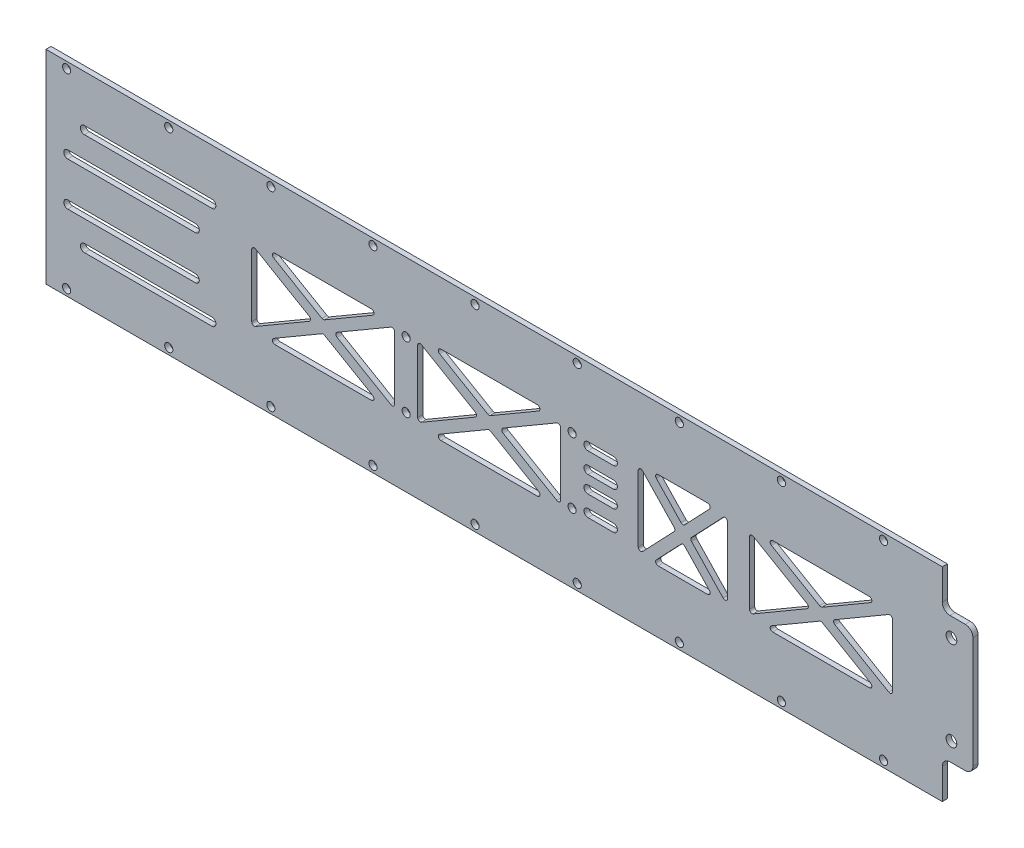
SolidWorks part; units mm, degrees
material "玻"
ref_plane "前视基准面" through (0, 0, 0) normal (0, 0, 1) x (1, 0, 0)
ref_plane "上视基准面" through (0, 0, 0) normal (0, 1, 0) x (1, 0, 0)
ref_plane "右视基准面" through (0, 0, 0) normal (1, 0, 0) x (0, 0, -1)
sketch "草图1" plane through (0, 0, 0) normal (0, 0, 1) x (1, 0, 0)
  line L0 (177.5, -27.83) -> (177.5, -39.83)
  line L1 (-177.5, 39.83) -> (177.5, 39.83)
  line L2 (-177.5, 39.83) -> (-177.5, -39.83)
  line L3 (-177.5, -39.83) -> (177.5, -39.83)
  line L4 (177.5, 39.83) -> (177.5, 27.83)
  line L5 (-177.5, 39.83) -> (177.5, -39.83) construction
  line L6 (-177.5, -39.83) -> (177.5, 39.83) construction
  line L7 (180.5, 24.83) -> (186.5, 24.83)
  line L9 (180.5, -24.83) -> (186.5, -24.83)
  line L10 (189.5, 21.83) -> (189.5, -21.83)
  arc A0 (186.5, -24.83) -> (189.5, -21.83) centre (186.5, -21.83) ccw
  arc A1 (186.5, 24.83) -> (189.5, 21.83) centre (186.5, 21.83) cw
  arc A2 (177.5, -27.83) -> (180.5, -24.83) centre (180.5, -27.83) cw
  arc A3 (180.5, 24.83) -> (177.5, 27.83) centre (180.5, 27.83) cw
  point P0 (0, 0)
  point P12 (189.5, -24.83)
  point P17 (177.5, -24.83)
  dimension "D6" = 3
  dimension "D1" = 79.66
  dimension "D2" = 355
  dimension "D3" = 15
  dimension "D4" = 15
  dimension "D5" = 12
extrude "凸台-拉伸1" add sketch "草图1" along normal blind 2
sketch "草图2" plane through (0, 0, 0) normal (0, 0, -1) x (-1, 0, 0)
  line L0 (0, 0) -> (157.1428, 0) construction
  line L1 (0, 0) -> (0, 112.2991) construction
  line L2 (-177.5, 39.83) -> (177.5, 39.83) construction
  line L3 (177.5, 39.83) -> (177.5, -39.83) construction
  line L4 (-189.5, -21.83) -> (-189.5, 21.83) construction
  line L5 (177.5, 39.83) -> (177.5, -39.83) construction
  circle A1 centre (165.5, 37.3) radius 1.6
  circle A2 centre (125.5, 37.3) radius 1.6
  circle A3 centre (85.5, 37.3) radius 1.6
  circle A4 centre (45.5, 37.3) radius 1.6
  circle A5 centre (5.5, 37.3) radius 1.6
  circle A6 centre (-34.5, 37.3) radius 1.6
  circle A7 centre (-74.5, 37.3) radius 1.6
  circle A8 centre (-114.5, 37.3) radius 1.6
  circle A9 centre (-154.5, 37.3) radius 1.6
  circle A10 centre (-154.5, -37.3) radius 1.6
  circle A11 centre (-114.5, -37.3) radius 1.6
  circle A12 centre (-74.5, -37.3) radius 1.6
  circle A13 centre (-34.5, -37.3) radius 1.6
  circle A14 centre (5.5, -37.3) radius 1.6
  circle A15 centre (45.5, -37.3) radius 1.6
  circle A16 centre (85.5, -37.3) radius 1.6
  circle A17 centre (125.5, -37.3) radius 1.6
  circle A18 centre (165.5, -37.3) radius 1.6
  circle A19 centre (-181.1, 17.5) radius 2.1
  circle A20 centre (-181.1, -17.5) radius 2.1
  circle A21 centre (141.2, 18.5) radius 2.1
  circle A22 centre (141.2, -18.5) radius 2.1
  circle A23 centre (98.9, 17.5) radius 2.1
  circle A24 centre (98.9, -17.5) radius 2.1
  circle A25 centre (32.5, 12.83) radius 1.6
  circle A26 centre (-32.5, 12.83) radius 1.6
  circle A27 centre (-32.5, -12.83) radius 1.6
  circle A28 centre (32.5, -12.83) radius 1.6
  dimension "D1" = 3.2
  dimension "D2" = 12
  dimension "D3" = 37.3
  dimension "D5" = 40
  dimension "D6" = 4.2
  dimension "D7" = 8.4
  dimension "D8" = 17.5
  dimension "D9" = 4.2
  dimension "D10" = 36.3
  dimension "D11" = 18.5
  dimension "D12" = 4.2
  dimension "D13" = 78.6
  dimension "D14" = 17.5
  dimension "D15" = 3.2
  dimension "D16" = 27
  dimension "D17" = 145
  dimension "D19" = 65
  dimension "D4" = 9
  dimension "D18" = 2
extrude "切除-拉伸1" cut sketch "草图2" against normal through all
sketch "草图4" plane through (0, 0, 2) normal (0, 0, 1) x (1, 0, 0)
  line L0 (-30, 15.5) -> (30, 15.5)
  line L1 (-30, 17.5) -> (30, 17.5)
  line L2 (-30, 17.5) -> (-30, -17.5)
  line L3 (-30, -17.5) -> (30, -17.5)
  line L4 (30, 17.5) -> (30, -17.5)
  line L5 (-30, 17.5) -> (30, -17.5) construction
  line L6 (-30, -17.5) -> (30, 17.5) construction
  line L7 (-31.0077, 15.7724) -> (28.9923, -19.2276)
  line L8 (-28.9923, -19.2276) -> (31.0077, 15.7724)
  line L9 (-32, 17.5) -> (-32, -17.5)
  line L10 (-30, -19.5) -> (30, -19.5)
  line L11 (28, 17.5) -> (28, -17.5)
  line L12 (-30, 19.5) -> (30, 19.5)
  line L13 (-28.9923, 19.2276) -> (31.0077, -15.7724)
  line L14 (-31.0077, -15.7724) -> (28.9923, 19.2276)
  line L15 (-28, 17.5) -> (-28, -17.5)
  line L16 (-30, -15.5) -> (30, -15.5)
  line L17 (32, 17.5) -> (32, -17.5)
  line L18 (35, 15.5) -> (95, 15.5)
  line L19 (35, 17.5) -> (95, 17.5)
  line L20 (35, 17.5) -> (35, -17.5)
  line L21 (35, -17.5) -> (95, -17.5)
  line L22 (95, 17.5) -> (95, -17.5)
  line L23 (33.9923, 15.7724) -> (93.9923, -19.2276)
  line L24 (36.0077, -19.2276) -> (96.0077, 15.7724)
  line L25 (33, 17.5) -> (33, -17.5)
  line L26 (35, -19.5) -> (95, -19.5)
  line L27 (93, 17.5) -> (93, -17.5)
  line L28 (35, 19.5) -> (95, 19.5)
  line L29 (36.0077, 19.2276) -> (96.0077, -15.7724)
  line L30 (33.9923, -15.7724) -> (93.9923, 19.2276)
  line L31 (37, 17.5) -> (37, -17.5)
  line L32 (35, -15.5) -> (95, -15.5)
  line L33 (97, 17.5) -> (97, -17.5)
  line L34 (35, 17.5) -> (95, -17.5) construction
  line L35 (35, -17.5) -> (95, 17.5) construction
  line L36 (-95, 15.5) -> (-35, 15.5)
  line L37 (-95, 17.5) -> (-35, 17.5)
  line L38 (-95, 17.5) -> (-95, -17.5)
  line L39 (-95, -17.5) -> (-35, -17.5)
  line L40 (-35, 17.5) -> (-35, -17.5)
  line L41 (-96.0077, 15.7724) -> (-36.0077, -19.2276)
  line L42 (-93.9923, -19.2276) -> (-33.9923, 15.7724)
  line L43 (-97, 17.5) -> (-97, -17.5)
  line L44 (-95, -19.5) -> (-35, -19.5)
  line L45 (-37, 17.5) -> (-37, -17.5)
  line L46 (-95, 19.5) -> (-35, 19.5)
  line L47 (-93.9923, 19.2276) -> (-33.9923, -15.7724)
  line L48 (-96.0077, -15.7724) -> (-36.0077, 19.2276)
  line L49 (-93, 17.5) -> (-93, -17.5)
  line L50 (-95, -15.5) -> (-35, -15.5)
  line L51 (-33, 17.5) -> (-33, -17.5)
  line L52 (-95, 17.5) -> (-35, -17.5) construction
  line L53 (-95, -17.5) -> (-35, 17.5) construction
  line L54 (100, 15.5) -> (160, 15.5)
  line L55 (100, 17.5) -> (160, 17.5)
  line L56 (100, 17.5) -> (100, -17.5)
  line L57 (100, -17.5) -> (160, -17.5)
  line L58 (160, 17.5) -> (160, -17.5)
  line L59 (98.9923, 15.7724) -> (158.9923, -19.2276)
  line L60 (101.0077, -19.2276) -> (161.0077, 15.7724)
  line L61 (98, 17.5) -> (98, -17.5)
  line L62 (100, -19.5) -> (160, -19.5)
  line L63 (158, 17.5) -> (158, -17.5)
  line L64 (100, 19.5) -> (160, 19.5)
  line L65 (101.0077, 19.2276) -> (161.0077, -15.7724)
  line L66 (98.9923, -15.7724) -> (158.9923, 19.2276)
  line L67 (102, 17.5) -> (102, -17.5)
  line L68 (100, -15.5) -> (160, -15.5)
  line L69 (162, 17.5) -> (162, -17.5)
  line L70 (100, 17.5) -> (160, -17.5) construction
  line L71 (100, -17.5) -> (160, 17.5) construction
  line L72 (0, 0) -> (267.4149, 0) construction
  line L73 (-127.5, -17.5) -> (-112.5, -17.5)
  line L74 (-127.5, -17.5) -> (-127.5, 17.5)
  line L75 (-127.5, 17.5) -> (-112.5, 17.5)
  line L76 (-112.5, -17.5) -> (-112.5, 17.5)
  line L77 (-127.5, -17.5) -> (-112.5, 17.5) construction
  line L78 (-127.5, 17.5) -> (-112.5, -17.5) construction
  line L79 (0, 0) -> (0, 160.2429) construction
  line L80 (-177.5, 39.83) -> (-177.5, -39.83) construction
  line L81 (-167.5, -17.5) -> (-167.5, 17.5)
  line L82 (-167.5, -17.5) -> (-152.5, -17.5)
  line L83 (-152.5, -17.5) -> (-152.5, 17.5)
  line L84 (-167.5, 17.5) -> (-152.5, 17.5)
  arc A0 (-30, 15.5) -> (-30, 19.5) centre (-30, 17.5) cw
  arc A1 (30, 15.5) -> (30, 19.5) centre (30, 17.5) ccw
  arc A2 (-31.0077, 15.7724) -> (-28.9923, 19.2276) centre (-30, 17.5) cw
  arc A3 (28.9923, -19.2276) -> (31.0077, -15.7724) centre (30, -17.5) ccw
  arc A4 (-28.9923, -19.2276) -> (-31.0077, -15.7724) centre (-30, -17.5) cw
  arc A5 (31.0077, 15.7724) -> (28.9923, 19.2276) centre (30, 17.5) ccw
  arc A6 (-32, 17.5) -> (-28, 17.5) centre (-30, 17.5) cw
  arc A7 (-32, -17.5) -> (-28, -17.5) centre (-30, -17.5) ccw
  arc A8 (-30, -19.5) -> (-30, -15.5) centre (-30, -17.5) cw
  arc A9 (30, -19.5) -> (30, -15.5) centre (30, -17.5) ccw
  arc A10 (28, 17.5) -> (32, 17.5) centre (30, 17.5) cw
  arc A11 (28, -17.5) -> (32, -17.5) centre (30, -17.5) ccw
  arc A12 (35, 15.5) -> (35, 19.5) centre (35, 17.5) cw
  arc A13 (95, 15.5) -> (95, 19.5) centre (95, 17.5) ccw
  arc A14 (33.9923, 15.7724) -> (36.0077, 19.2276) centre (35, 17.5) cw
  arc A15 (93.9923, -19.2276) -> (96.0077, -15.7724) centre (95, -17.5) ccw
  arc A16 (36.0077, -19.2276) -> (33.9923, -15.7724) centre (35, -17.5) cw
  arc A17 (96.0077, 15.7724) -> (93.9923, 19.2276) centre (95, 17.5) ccw
  arc A18 (33, 17.5) -> (37, 17.5) centre (35, 17.5) cw
  arc A19 (33, -17.5) -> (37, -17.5) centre (35, -17.5) ccw
  arc A20 (35, -19.5) -> (35, -15.5) centre (35, -17.5) cw
  arc A21 (95, -19.5) -> (95, -15.5) centre (95, -17.5) ccw
  arc A22 (93, 17.5) -> (97, 17.5) centre (95, 17.5) cw
  arc A23 (93, -17.5) -> (97, -17.5) centre (95, -17.5) ccw
  arc A24 (-95, 15.5) -> (-95, 19.5) centre (-95, 17.5) cw
  arc A25 (-35, 15.5) -> (-35, 19.5) centre (-35, 17.5) ccw
  arc A26 (-96.0077, 15.7724) -> (-93.9923, 19.2276) centre (-95, 17.5) cw
  arc A27 (-36.0077, -19.2276) -> (-33.9923, -15.7724) centre (-35, -17.5) ccw
  arc A28 (-93.9923, -19.2276) -> (-96.0077, -15.7724) centre (-95, -17.5) cw
  arc A29 (-33.9923, 15.7724) -> (-36.0077, 19.2276) centre (-35, 17.5) ccw
  arc A30 (-97, 17.5) -> (-93, 17.5) centre (-95, 17.5) cw
  arc A31 (-97, -17.5) -> (-93, -17.5) centre (-95, -17.5) ccw
  arc A32 (-95, -19.5) -> (-95, -15.5) centre (-95, -17.5) cw
  arc A33 (-35, -19.5) -> (-35, -15.5) centre (-35, -17.5) ccw
  arc A34 (-37, 17.5) -> (-33, 17.5) centre (-35, 17.5) cw
  arc A35 (-37, -17.5) -> (-33, -17.5) centre (-35, -17.5) ccw
  arc A36 (100, 15.5) -> (100, 19.5) centre (100, 17.5) cw
  arc A37 (160, 15.5) -> (160, 19.5) centre (160, 17.5) ccw
  arc A38 (98.9923, 15.7724) -> (101.0077, 19.2276) centre (100, 17.5) cw
  arc A39 (158.9923, -19.2276) -> (161.0077, -15.7724) centre (160, -17.5) ccw
  arc A40 (101.0077, -19.2276) -> (98.9923, -15.7724) centre (100, -17.5) cw
  arc A41 (161.0077, 15.7724) -> (158.9923, 19.2276) centre (160, 17.5) ccw
  arc A42 (98, 17.5) -> (102, 17.5) centre (100, 17.5) cw
  arc A43 (98, -17.5) -> (102, -17.5) centre (100, -17.5) ccw
  arc A44 (100, -19.5) -> (100, -15.5) centre (100, -17.5) cw
  arc A45 (160, -19.5) -> (160, -15.5) centre (160, -17.5) ccw
  arc A46 (158, 17.5) -> (162, 17.5) centre (160, 17.5) cw
  arc A47 (158, -17.5) -> (162, -17.5) centre (160, -17.5) ccw
  point P0 (0, 0)
  point P30 (-120, 0)
  point P31 (65, 0)
  point P60 (130, 0)
  point P61 (-65, 0)
  dimension "D1" = 60
  dimension "D2" = 35
  dimension "D6" = 1
  dimension "D8" = 1
  dimension "D10" = 1
  dimension "D11" = 15
  dimension "D12" = 35
  dimension "D13" = 50
  dimension "D15" = 25
  dimension "D3" = 2
  dimension "D4" = 2
  dimension "D5" = 2
  dimension "D7" = 2
  dimension "D9" = 2
  dimension "D14" = 2
extrude "切除-拉伸2" cut sketch "草图4" against normal through all contours L13 L14 L0 | L7 L15 L14 | L8 L13 L11 | L8 L16 L7 | L29 L30 L18 | L23 L31 L30 | L24 L29 L27 | L24 L32 L23 | L47 L48 L36 | L41 L49 L48 | L42 L47 L45 | L42 L50 L41 | L65 L66 L54 | L59 L67 L66 | L60 L68 L59 | L60 L65 L63 | L84 L81 L82 L83 | L73 L76 L75 L74
fillet "圆角1" radius 1 56 edges at (-28, -14.0179, 1) (-3.9693, 0, 1) (28, -14.0179, 1) (3.9693, 0, 1) (28, 14.0179, 1) (22.6022, -15.5, 1) (-22.6022, -15.5, 1) (0, -2.3154, 1) (-28, 14.0179, 1) (22.6022, 15.5, 1) (0, 2.3154, 1) (-22.6022, 15.5, 1) (87.6022, -15.5, 1) (42.3978, -15.5, 1) (65, -2.3154, 1) (93, -14.0179, 1) (68.9693, 0, 1) (93, 14.0179, 1) (37, -14.0179, 1) (37, 14.0179, 1) (61.0307, 0, 1) (87.6022, 15.5, 1) (65, 2.3154, 1) (42.3978, 15.5, 1) (-42.3978, -15.5, 1) (-87.6022, -15.5, 1) (-65, -2.3154, 1) (-37, -14.0179, 1) (-61.0307, 0, 1) (-37, 14.0179, 1) (-93, -14.0179, 1) (-93, 14.0179, 1) (-68.9693, 0, 1) (-42.3978, 15.5, 1) (-65, 2.3154, 1) (-87.6022, 15.5, 1) (152.6022, -15.5, 1) (107.3978, -15.5, 1) (130, -2.3154, 1) (102, -14.0179, 1) (102, 14.0179, 1) (126.0307, 0, 1) (158, -14.0179, 1) (133.9693, 0, 1) (158, 14.0179, 1) (152.6022, 15.5, 1) (130, 2.3154, 1) (107.3978, 15.5, 1) (-127.5, -17.5, 1) (-112.5, 17.5, 1) (-112.5, -17.5, 1) (-127.5, 17.5, 1) (-152.5, -17.5, 1) (-167.5, -17.5, 1) (-152.5, 17.5, 1) (-167.5, 17.5, 1)
sketch "草图6" plane through (0, 0, 2) normal (0, 0, 1) x (1, 0, 0)
  line L0 (181.1, 17.5) -> (181.1, -17.5)
  line L1 (114.5, 37.3) -> (154.5, 37.3)
  line L2 (-165.5, 37.3) -> (-177.5, 37.3)
  line L3 (-177.5, 39.83) -> (-177.5, -39.83) construction
  line L4 (181.1, 17.5) -> (189.5, 17.5)
  line L5 (189.5, -21.83) -> (189.5, 21.83) construction
  line L6 (114.5, 37.3) -> (114.5, 39.83)
  line L7 (177.5, 39.83) -> (-177.5, 39.83) construction
  line L8 (154.5, 37.3) -> (154.5, -37.3)
  line L9 (32.5, 12.83) -> (32.5, -12.83)
  line L10 (32.5, 12.83) -> (-32.5, 12.83)
  line L11 (-98.9, 17.5) -> (-98.9, -17.5)
  line L12 (-141.2, 18.5) -> (-98.9, 17.5)
  line L13 (-32.5, 12.83) -> (-177.5, 12.83)
  line L14 (-98.9, -17.5) -> (-177.5, -17.5)
  dimension "D1" = 35
  dimension "D2" = 12
  dimension "D3" = 40
  dimension "D4" = 8.4
  dimension "D5" = 2.53
  dimension "D6" = 74.6
  dimension "D7" = 25.66
  dimension "D8" = 65
  dimension "D9" = 35
  dimension "D10" = 145
  dimension "D11" = 78.6
sketch "草图7" plane through (0, 0, 0) normal (0, 0, 1) x (1, 0, 0)
  line L0 (37, 12.2769) -> (37, -12.2769) construction
  line L1 (37, 17.3182) -> (93.0723, 17.3182)
  line L2 (37, 17.3182) -> (37, -17.8709)
  line L3 (37, -17.8709) -> (93.0723, -17.8709)
  line L4 (93.0723, 17.3182) -> (93.0723, -17.8709)
  dimension "D1" = 0
extrude "凸台-拉伸2" add sketch "草图7" along normal blind 2
sketch "草图8" plane through (0, 0, 0) normal (0, 0, 1) x (1, 0, 0)
  line L0 (38.7, -3.33) -> (48.7, -3.33) construction
  line L1 (38.7, -1.78) -> (48.7, -1.78)
  line L2 (38.7, -4.88) -> (48.7, -4.88)
  line L3 (38.7, -11.33) -> (48.7, -11.33) construction
  line L4 (38.7, -9.78) -> (48.7, -9.78)
  line L5 (38.7, -12.88) -> (48.7, -12.88)
  line L6 (-177.5, -39.83) -> (177.5, -39.83) construction
  line L7 (37, 12.2769) -> (37, -12.2769) construction
  line L8 (71.9824, 39.83) -> (71.9824, -39.83) construction
  line L9 (177.5, 39.83) -> (-177.5, 39.83) construction
  line L10 (71.9824, 0) -> (-49928.0176, 0) construction
  line L11 (38.7, 11.33) -> (48.7, 11.33) construction
  line L12 (38.7, 9.78) -> (48.7, 9.78)
  line L13 (38.7, 12.88) -> (48.7, 12.88)
  line L14 (38.7, 3.33) -> (48.7, 3.33) construction
  line L15 (38.7, 1.78) -> (48.7, 1.78)
  line L16 (38.7, 4.88) -> (48.7, 4.88)
  arc A0 (38.7, -1.78) -> (38.7, -4.88) centre (38.7, -3.33) ccw
  arc A1 (48.7, -4.88) -> (48.7, -1.78) centre (48.7, -3.33) ccw
  arc A2 (38.7, -9.78) -> (38.7, -12.88) centre (38.7, -11.33) ccw
  arc A3 (48.7, -12.88) -> (48.7, -9.78) centre (48.7, -11.33) ccw
  arc A4 (38.7, 9.78) -> (38.7, 12.88) centre (38.7, 11.33) cw
  arc A5 (48.7, 12.88) -> (48.7, 9.78) centre (48.7, 11.33) cw
  arc A6 (38.7, 1.78) -> (38.7, 4.88) centre (38.7, 3.33) cw
  arc A7 (48.7, 4.88) -> (48.7, 1.78) centre (48.7, 3.33) cw
  point P2 (43.7, -3.33)
  point P9 (43.7, -11.33)
  point P24 (71.9824, 0)
  point P27 (43.7, 11.33)
  point P34 (43.7, 3.33)
  dimension "D1" = 1.55
  dimension "D4" = 1.55
  dimension "D2" = 10
  dimension "D3" = 10
  dimension "D5" = 28.5
  dimension "D6" = 8
  dimension "D7" = 1.7
  dimension "D8" = 1.7
extrude "切除-拉伸3" cut sketch "草图8" along normal blind 2
sketch "草图9" plane through (0, 0, 0) normal (0, 0, 1) x (1, 0, 0)
  line L1 (-170.3831, 20.8276) -> (-149.384, 20.8276)
  line L2 (-170.3831, 20.8276) -> (-170.3831, -21.6013)
  line L3 (-170.3831, -21.6013) -> (-149.384, -21.6013)
  line L4 (-149.384, 20.8276) -> (-149.384, -21.6013)
  line L5 (-131.1848, 20.1815) -> (-110.2934, 20.1815)
  line L6 (-131.1848, 20.1815) -> (-131.1848, -20.5245)
  line L7 (-131.1848, -20.5245) -> (-110.2934, -20.5245)
  line L8 (-110.2934, 20.1815) -> (-110.2934, -20.5245)
extrude "凸台-拉伸3" add sketch "草图9" along normal blind 2
sketch "草图10" plane through (0, 0, 2) normal (0, 0, 1) x (1, 0, 0)
  line L0 (-151.0024, 20.0044) -> (-120.6456, 20.0044)
  line L1 (-151.0024, 20.0044) -> (-165.1964, 20.0044)
  line L2 (-173.5841, 39.83) -> (-173.5841, -39.83)
  line L3 (177.5, 39.83) -> (-177.5, 39.83) construction
  line L4 (-177.5, -39.83) -> (177.5, -39.83) construction
  line L5 (-173.5841, -39.83) -> (-177.5, -39.83)
  line L6 (-177.5, -39.83) -> (-177.5, 39.83)
  line L7 (-177.5, 39.83) -> (-173.5841, 39.83)
  circle A0 centre (-149.5024, 20) radius 1.5 construction
extrude "切除-拉伸4" cut sketch "草图10" against normal blind 2 contours L7 L6 L5 L2
sketch "草图12" plane through (0, 0, 2) normal (0, 0, 1) x (1, 0, 0)
  line L1 (-150.5318, 25.2283) -> (-95.1803, 25.2283)
  line L2 (-150.5318, 25.2283) -> (-150.5318, -21.9389)
  line L3 (-150.5318, -21.9389) -> (-95.1803, -21.9389)
  line L4 (-95.1803, 25.2283) -> (-95.1803, -21.9389)
extrude "凸台-拉伸4" add sketch "草图12" against normal blind 2
sketch "草图13" plane through (0, 0, 2) normal (0, 0, 1) x (1, 0, 0)
  line L0 (-158.5841, 19.95) -> (-108.5841, 19.95) construction
  line L1 (-158.5841, 21.5) -> (-108.5841, 21.5)
  line L2 (-158.5841, 18.4) -> (-108.5841, 18.4)
  line L3 (-165.0841, 8.45) -> (-115.0841, 8.45) construction
  line L4 (-165.0841, 10) -> (-115.0841, 10)
  line L5 (-165.0841, 6.9) -> (-115.0841, 6.9)
  line L6 (-165.0841, -8.55) -> (-115.0841, -8.55) construction
  line L7 (-165.0841, -7) -> (-115.0841, -7)
  line L8 (-165.0841, -10.1) -> (-115.0841, -10.1)
  line L9 (-158.5841, -20.05) -> (-108.5841, -20.05) construction
  line L10 (-158.5841, -18.5) -> (-108.5841, -18.5)
  line L11 (-158.5841, -21.6) -> (-108.5841, -21.6)
  arc A0 (-158.5841, 21.5) -> (-158.5841, 18.4) centre (-158.5841, 19.95) ccw
  arc A1 (-108.5841, 18.4) -> (-108.5841, 21.5) centre (-108.5841, 19.95) ccw
  arc A2 (-165.0841, 10) -> (-165.0841, 6.9) centre (-165.0841, 8.45) ccw
  arc A3 (-115.0841, 6.9) -> (-115.0841, 10) centre (-115.0841, 8.45) ccw
  arc A4 (-165.0841, -7) -> (-165.0841, -10.1) centre (-165.0841, -8.55) ccw
  arc A5 (-115.0841, -10.1) -> (-115.0841, -7) centre (-115.0841, -8.55) ccw
  arc A6 (-158.5841, -18.5) -> (-158.5841, -21.6) centre (-158.5841, -20.05) ccw
  arc A7 (-108.5841, -21.6) -> (-108.5841, -18.5) centre (-108.5841, -20.05) ccw
  point P4 (-133.5841, 19.95)
  point P9 (-140.0841, 8.45)
  point P18 (-140.0841, -8.55)
  point P27 (-133.5841, -20.05)
  dimension "D1" = 1.55
  dimension "D2" = 1.55
  dimension "D3" = 1.55
  dimension "D4" = 1.55
extrude "切除-拉伸5" cut sketch "草图13" against normal blind 2
sketch "草图14" plane through (0, 0, 0) normal (0, 0, 1) x (1, 0, 0)
  line L0 (5.4151, 15.5) -> (50005.4151, 15.5) construction
  line L1 (78.6435, 0) -> (93.3975, 15.5)
  line L2 (10.6918, -15.5) -> (50010.6918, -15.5) construction
  line L3 (73.1514, 0) -> (58.3975, -15.5)
  line L5 (93.3975, 15.5) -> (58.3975, 15.5)
  line L6 (93.3975, 15.5) -> (93.3975, -15.5)
  line L7 (93.3975, -15.5) -> (58.3975, -15.5)
  line L8 (58.3975, 15.5) -> (58.3975, -15.5)
  line L12 (63.8895, 15.5) -> (75.8975, 2.8849)
  line L13 (58.3975, 15.5) -> (73.1514, 0)
  line L14 (63.8895, -15.5) -> (75.8975, -2.8849)
  line L15 (87.9054, 15.5) -> (75.8975, 2.8849)
  line L17 (78.6435, 0) -> (93.3975, -15.5)
  line L20 (75.8975, -2.8849) -> (87.9054, -15.5)
  point P4 (75.8975, 0)
  dimension "D1" = 35
extrude "切除-拉伸6" cut sketch "草图14" along normal blind 2 contours L13 L8 L3 | L1 L17 L6 | L20 L14 L7 | L15 L5 L12
fillet "圆角2" radius 1 12 edges at (58.3975, -15.5, 1) (63.8895, -15.5, 1) (87.9054, -15.5, 1) (93.3975, -15.5, 1) (75.8975, -2.8849, 1) (78.6435, 0, 1) (75.8975, 2.8849, 1) (73.1514, 0, 1) (58.3975, 15.5, 1) (63.8895, 15.5, 1) (87.9054, 15.5, 1) (93.3975, 15.5, 1)
